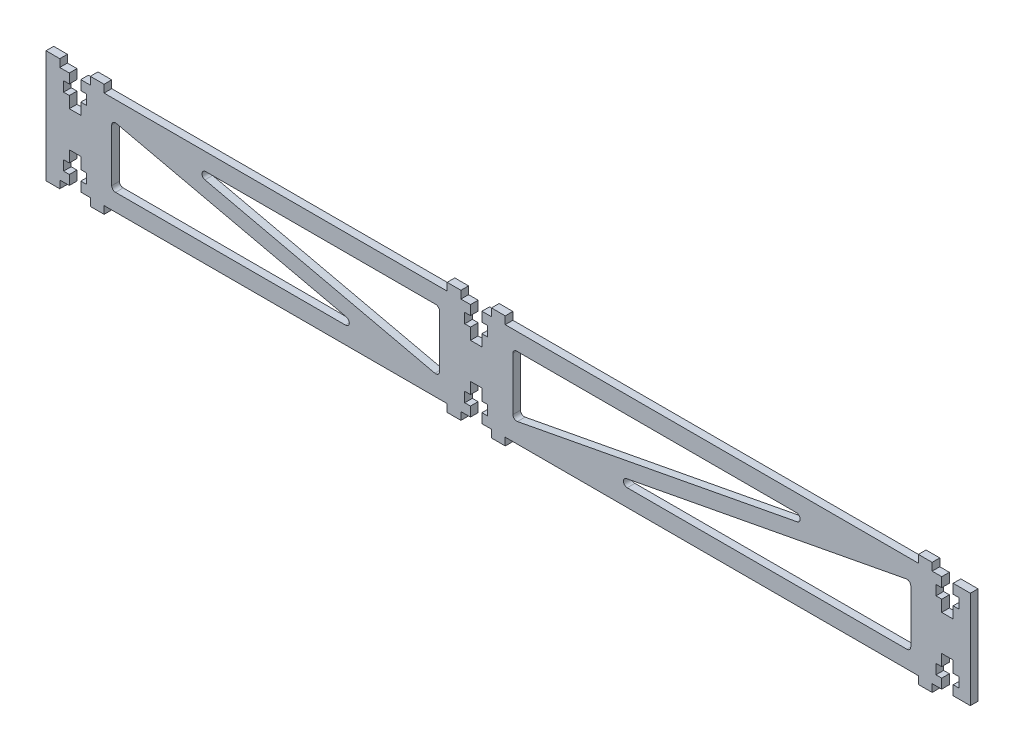
SolidWorks part; units mm, degrees
ref_plane "前视基准面" through (0, 0, 0) normal (0, 0, 1) x (1, 0, 0)
ref_plane "上视基准面" through (0, 0, 0) normal (0, 1, 0) x (1, 0, 0)
ref_plane "右视基准面" through (0, 0, 0) normal (1, 0, 0) x (0, 0, -1)
sketch "草图2" plane through (0, 0, 0) normal (0, 0, 1) x (1, 0, 0)
  line L12 (-24.2469, 6.3576) -> (-21.7469, 6.3576)
  line L24 (-29.7469, 8.3576) -> (-33.3469, 8.3576)
  line L25 (-29.7469, 6.3576) -> (-27.2469, 6.3576)
  line L28 (-29.7469, 8.3576) -> (-29.7469, 6.3576)
  line L30 (-28.7469, 3.8576) -> (-28.7469, 1.2576)
  line L31 (-28.7469, 1.2576) -> (-27.2469, 1.2576)
  line L32 (-27.2469, 1.2576) -> (-27.2469, -1.7424)
  line L33 (-24.2469, 1.2576) -> (-24.2469, -1.7424)
  line L34 (-22.7469, 1.2576) -> (-24.2469, 1.2576)
  line L35 (-22.7469, 3.8576) -> (-22.7469, 1.2576)
  line L36 (-27.2469, 3.8576) -> (-28.7469, 3.8576)
  line L37 (-27.2469, -1.7424) -> (-24.2469, -1.7424)
  line L38 (-24.2469, 3.8576) -> (-22.7469, 3.8576)
  line L39 (-27.2469, 3.8576) -> (-27.2469, 6.3576)
  line L40 (-24.2469, 3.8576) -> (-24.2469, 6.3576)
  line L52 (-18.1469, 6.3576) -> (71.6531, 6.3576)
  line L53 (-21.7469, 6.3576) -> (-21.7469, 8.3576)
  line L54 (-21.7469, 8.3576) -> (-18.1469, 8.3576)
  line L90 (80.7531, 6.3576) -> (83.2531, 6.3576)
  line L94 (-18.1469, 8.3576) -> (-18.1469, 6.3576)
  line L97 (75.2531, 8.3576) -> (71.6531, 8.3576)
  line L98 (71.6531, -19.1424) -> (-18.1469, -19.1424)
  line L131 (79.2531, -6.3924) -> (159.2531, -6.3924) construction
  line L137 (-18.1469, -21.1424) -> (-18.1469, -19.1424)
  line L138 (-21.7469, -21.1424) -> (-18.1469, -21.1424)
  line L141 (-21.7469, -19.1424) -> (-21.7469, -21.1424)
  line L142 (-24.2469, -16.6424) -> (-24.2469, -19.1424)
  line L143 (-27.2469, -16.6424) -> (-27.2469, -19.1424)
  line L144 (-24.2469, -16.6424) -> (-22.7469, -16.6424)
  line L145 (-27.2469, -11.0424) -> (-24.2469, -11.0424)
  line L146 (-27.2469, -16.6424) -> (-28.7469, -16.6424)
  line L147 (-22.7469, -16.6424) -> (-22.7469, -14.0424)
  line L148 (-22.7469, -14.0424) -> (-24.2469, -14.0424)
  line L149 (-24.2469, -14.0424) -> (-24.2469, -11.0424)
  line L150 (-27.2469, -14.0424) -> (-27.2469, -11.0424)
  line L151 (-28.7469, -14.0424) -> (-27.2469, -14.0424)
  line L152 (-28.7469, -16.6424) -> (-28.7469, -14.0424)
  line L153 (-29.7469, -21.1424) -> (-29.7469, -19.1424)
  line L154 (-29.7469, -19.1424) -> (-27.2469, -19.1424)
  line L155 (-29.7469, -21.1424) -> (-33.3469, -21.1424)
  line L156 (-24.2469, -19.1424) -> (-21.7469, -19.1424)
  line L157 (75.2531, 6.3576) -> (77.7531, 6.3576)
  line L158 (75.2531, 8.3576) -> (75.2531, 6.3576)
  line L159 (76.2531, 3.8576) -> (76.2531, 1.2576)
  line L160 (76.2531, 1.2576) -> (77.7531, 1.2576)
  line L161 (77.7531, 1.2576) -> (77.7531, -1.7424)
  line L162 (80.7531, 1.2576) -> (80.7531, -1.7424)
  line L163 (82.2531, 1.2576) -> (80.7531, 1.2576)
  line L164 (82.2531, 3.8576) -> (82.2531, 1.2576)
  line L165 (77.7531, 3.8576) -> (76.2531, 3.8576)
  line L166 (77.7531, -1.7424) -> (80.7531, -1.7424)
  line L167 (80.7531, 3.8576) -> (82.2531, 3.8576)
  line L168 (77.7531, 3.8576) -> (77.7531, 6.3576)
  line L169 (80.7531, 3.8576) -> (80.7531, 6.3576)
  line L170 (79.2531, -1.7424) -> (79.2531, -11.0424) construction
  line L171 (83.2531, 6.3576) -> (83.2531, 8.3576)
  line L172 (83.2531, 8.3576) -> (86.8531, 8.3576)
  line L173 (86.8531, 8.3576) -> (86.8531, 6.3576)
  line L174 (86.8531, -21.1424) -> (86.8531, -19.1424)
  line L175 (83.2531, -21.1424) -> (86.8531, -21.1424)
  line L176 (83.2531, -19.1424) -> (83.2531, -21.1424)
  line L177 (80.7531, -16.6424) -> (80.7531, -19.1424)
  line L178 (77.7531, -16.6424) -> (77.7531, -19.1424)
  line L179 (80.7531, -16.6424) -> (82.2531, -16.6424)
  line L180 (77.7531, -11.0424) -> (80.7531, -11.0424)
  line L181 (77.7531, -16.6424) -> (76.2531, -16.6424)
  line L182 (82.2531, -16.6424) -> (82.2531, -14.0424)
  line L183 (82.2531, -14.0424) -> (80.7531, -14.0424)
  line L184 (80.7531, -14.0424) -> (80.7531, -11.0424)
  line L185 (77.7531, -14.0424) -> (77.7531, -11.0424)
  line L186 (76.2531, -14.0424) -> (77.7531, -14.0424)
  line L187 (76.2531, -16.6424) -> (76.2531, -14.0424)
  line L188 (75.2531, -21.1424) -> (75.2531, -19.1424)
  line L189 (75.2531, -19.1424) -> (77.7531, -19.1424)
  line L190 (75.2531, -21.1424) -> (71.6531, -21.1424)
  line L191 (80.7531, -19.1424) -> (83.2531, -19.1424)
  line L229 (-33.3469, 8.3576) -> (-33.3469, -21.1424)
  line L231 (71.6531, 8.3576) -> (71.6531, 6.3576)
  line L232 (71.6531, -21.1424) -> (71.6531, -19.1424)
  line L235 (159.2531, -6.3924) -> (202.5931, -6.3924) construction
  line L236 (204.0931, 6.3576) -> (206.5931, 6.3576)
  line L237 (198.5931, 6.3576) -> (201.0931, 6.3576)
  line L238 (198.5931, 8.3576) -> (198.5931, 6.3576)
  line L239 (199.5931, 3.8576) -> (199.5931, 1.2576)
  line L240 (199.5931, 1.2576) -> (201.0931, 1.2576)
  line L241 (201.0931, 1.2576) -> (201.0931, -1.7424)
  line L242 (204.0931, 1.2576) -> (204.0931, -1.7424)
  line L243 (205.5931, 1.2576) -> (204.0931, 1.2576)
  line L244 (205.5931, 3.8576) -> (205.5931, 1.2576)
  line L245 (201.0931, 3.8576) -> (199.5931, 3.8576)
  line L246 (201.0931, -1.7424) -> (204.0931, -1.7424)
  line L247 (204.0931, 3.8576) -> (205.5931, 3.8576)
  line L248 (201.0931, 3.8576) -> (201.0931, 6.3576)
  line L249 (204.0931, 3.8576) -> (204.0931, 6.3576)
  line L250 (202.5931, -1.7424) -> (202.5931, -11.0424) construction
  line L251 (206.5931, 6.3576) -> (208.5931, 6.3576)
  line L252 (208.5931, 6.3576) -> (208.5931, -19.1424)
  line L253 (204.0931, -16.6424) -> (204.0931, -19.1424)
  line L254 (201.0931, -16.6424) -> (201.0931, -19.1424)
  line L255 (204.0931, -16.6424) -> (205.5931, -16.6424)
  line L256 (201.0931, -11.0424) -> (204.0931, -11.0424)
  line L257 (201.0931, -16.6424) -> (199.5931, -16.6424)
  line L258 (205.5931, -16.6424) -> (205.5931, -14.0424)
  line L259 (205.5931, -14.0424) -> (204.0931, -14.0424)
  line L260 (204.0931, -14.0424) -> (204.0931, -11.0424)
  line L261 (201.0931, -14.0424) -> (201.0931, -11.0424)
  line L262 (199.5931, -14.0424) -> (201.0931, -14.0424)
  line L263 (199.5931, -16.6424) -> (199.5931, -14.0424)
  line L264 (198.5931, -21.1424) -> (198.5931, -19.1424)
  line L265 (198.5931, -19.1424) -> (201.0931, -19.1424)
  line L266 (204.0931, -19.1424) -> (206.5931, -19.1424)
  line L267 (202.5931, -6.3924) -> (204.0931, -6.3924) construction
  line L268 (198.5931, 8.3576) -> (194.9931, 8.3576)
  line L269 (194.9931, 8.3576) -> (194.9931, 6.3576)
  line L270 (198.5931, -21.1424) -> (194.9931, -21.1424)
  line L271 (194.9931, -21.1424) -> (194.9931, -19.1424)
  line L272 (208.5931, -19.1424) -> (206.5931, -19.1424)
  line L302 (86.8531, 6.3576) -> (194.9931, 6.3576)
  line L303 (194.9931, -19.1424) -> (86.8531, -19.1424)
  line L314 (-18.1469, 3.8576) -> (71.6531, -16.6424) construction
  line L325 (86.8531, 3.8576) -> (194.9931, 3.8576) construction
  line L326 (86.8531, 3.8576) -> (86.8531, -16.6424) construction
  line L327 (86.8531, -16.6424) -> (194.9931, -16.6424) construction
  line L328 (194.9931, 3.8576) -> (194.9931, -16.6424) construction
  line L329 (86.8531, -16.6424) -> (194.9931, 3.8576) construction
  line L336 (-18.1469, 3.8576) -> (71.6531, 3.8576) construction
  line L337 (-18.1469, 3.8576) -> (-18.1469, -16.6424) construction
  line L338 (-18.1469, -16.6424) -> (71.6531, -16.6424) construction
  line L339 (71.6531, 3.8576) -> (71.6531, -16.6424) construction
  line L340 (8.4741, 1.8576) -> (68.6531, 1.8576)
  line L341 (69.6531, 0.8576) -> (69.6531, -12.8804)
  line L342 (89.8531, 1.8576) -> (163.0605, 1.8576)
  line L343 (90.0394, -14.0028) -> (163.2468, -0.1249)
  line L344 (88.8531, 0.8576) -> (88.8531, -13.0203)
  line L345 (118.7857, -14.6424) -> (191.9931, -14.6424)
  line L346 (192.9931, 0.2355) -> (192.9931, -13.6424)
  line L347 (118.5994, -12.6599) -> (191.8069, 1.218)
  line L348 (88.8531, 1.8576) -> (88.8531, -14.2276) construction
  line L349 (88.8531, 1.8576) -> (173.7047, 1.8576) construction
  line L350 (88.8531, -14.2276) -> (173.7047, 1.8576) construction
  line L351 (108.1415, -14.6424) -> (192.9931, 1.4429) construction
  line L352 (192.9931, 1.4429) -> (192.9931, -14.6424) construction
  line L353 (108.1415, -14.6424) -> (192.9931, -14.6424) construction
  line L354 (8.2516, -0.1173) -> (68.4305, -13.8553)
  line L355 (-16.1469, 0.0956) -> (-16.1469, -13.6424)
  line L356 (-15.1469, -14.6424) -> (45.0321, -14.6424)
  line L357 (-14.9243, 1.0705) -> (45.2547, -12.6675)
  line L358 (-0.3996, 1.8576) -> (69.6531, -14.1344) construction
  line L359 (69.6531, 1.8576) -> (69.6531, -14.1344) construction
  line L360 (-0.3996, 1.8576) -> (69.6531, 1.8576) construction
  line L361 (-16.1469, -14.6424) -> (53.9058, -14.6424) construction
  line L362 (-16.1469, 1.3496) -> (53.9058, -14.6424) construction
  line L363 (-16.1469, 1.3496) -> (-16.1469, -14.6424) construction
  arc A40 (88.8531, 0.8576) -> (89.8531, 1.8576) centre (89.8531, 0.8576) cw
  arc A41 (90.0394, -14.0028) -> (88.8531, -13.0203) centre (89.8531, -13.0203) cw
  arc A42 (163.2468, -0.1249) -> (163.0605, 1.8576) centre (163.0605, 0.8576) ccw
  arc A43 (191.8069, 1.218) -> (192.9931, 0.2355) centre (191.9931, 0.2355) cw
  arc A44 (192.9931, -13.6424) -> (191.9931, -14.6424) centre (191.9931, -13.6424) cw
  arc A45 (118.7857, -14.6424) -> (118.5994, -12.6599) centre (118.7857, -13.6424) cw
  arc A46 (68.4305, -13.8553) -> (69.6531, -12.8804) centre (68.6531, -12.8804) ccw
  arc A47 (69.6531, 0.8576) -> (68.6531, 1.8576) centre (68.6531, 0.8576) ccw
  arc A48 (8.2516, -0.1173) -> (8.4741, 1.8576) centre (8.4741, 0.8576) cw
  arc A49 (45.0321, -14.6424) -> (45.2547, -12.6675) centre (45.0321, -13.6424) ccw
  arc A50 (-15.1469, -14.6424) -> (-16.1469, -13.6424) centre (-15.1469, -13.6424) cw
  arc A51 (-14.9243, 1.0705) -> (-16.1469, 0.0956) centre (-15.1469, 0.0956) ccw
  dimension "D1" = 2
  dimension "D2" = 2
  dimension "D3" = 1
  dimension "D4" = 2
  dimension "D5" = 2
  dimension "D6" = 1
  dimension "D7" = 1
  dimension "D8" = 1
  dimension "D9" = 1
extrude "凸台-拉伸1" add sketch "草图2" along normal blind 2
sketch "草图4" plane through (0, 6.3576, 0) normal (0, 1, 0) x (1, 0, 0)
  line L0 (-24.2469, -1) -> (-27.2469, -1)
  line L1 (-24.2469, -2) -> (-24.2469, 0) construction
  line L2 (-27.2469, -2) -> (-27.2469, 0) construction
  circle A0 centre (-25.7469, -1) radius 1.5
